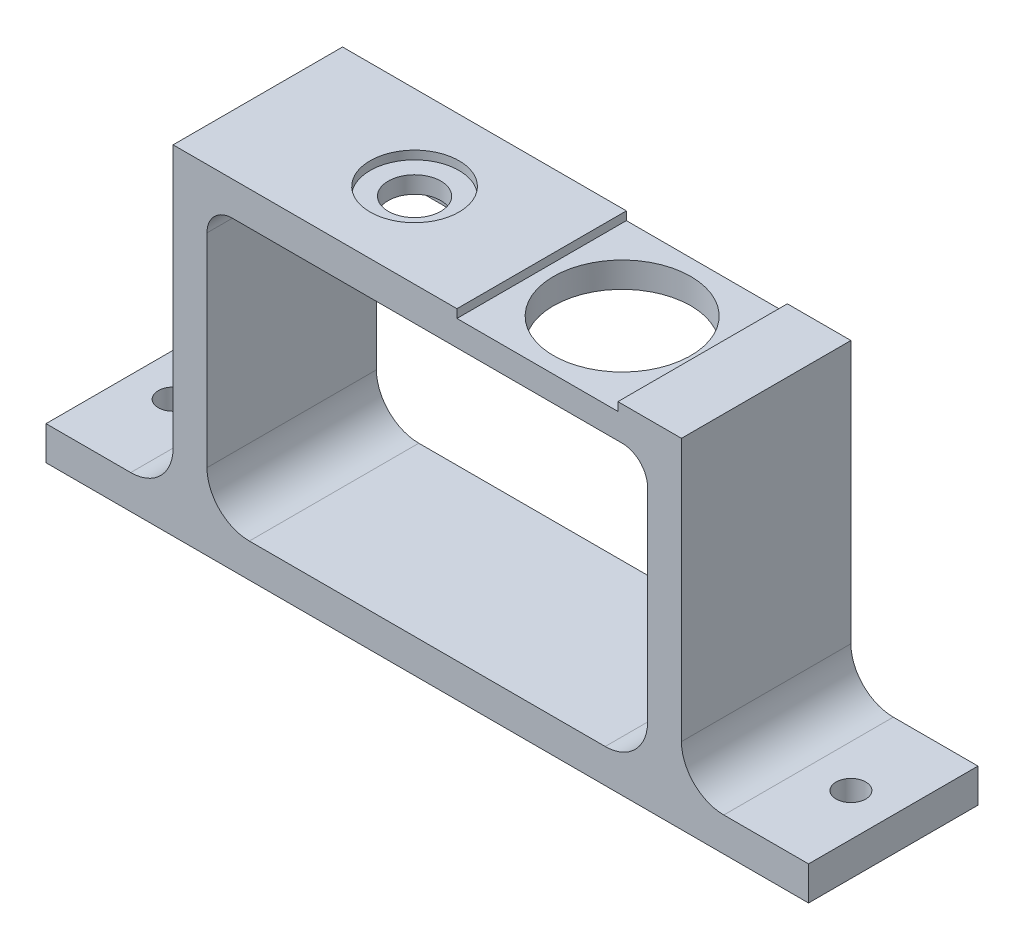
SolidWorks part; units mm, degrees
ref_plane "前视基准面" through (0, 0, 0) normal (0, 0, 1) x (1, 0, 0)
ref_plane "上视基准面" through (0, 0, 0) normal (0, 1, 0) x (1, 0, 0)
ref_plane "右视基准面" through (0, 0, 0) normal (1, 0, 0) x (0, 0, -1)
sketch "草图1" plane through (0, 0, 0) normal (0, 1, 0) x (1, 0, 0)
  line L0 (45, 10) -> (45, 29.8353) construction
  line L1 (0, 0) -> (90, 0)
  line L2 (0, 0) -> (0, 20)
  line L3 (0, 20) -> (90, 20)
  line L4 (90, 0) -> (90, 20)
  line L5 (0, 0) -> (90, 20) construction
  line L6 (0, 20) -> (90, 0) construction
  circle A0 centre (85, 10) radius 1.75
  circle A3 centre (5, 10) radius 1.75
  point P4 (45, 10)
  dimension "D4" = 5
  dimension "D5" = 3.5
  dimension "D7" = 10
  dimension "D1" = 20
  dimension "D2" = 90
extrude "凸台-拉伸1" add sketch "草图1" along normal blind 4
sketch "草图2" plane through (0, 4, 0) normal (0, 1, 0) x (1, 0, 0)
  line L0 (90, 20) -> (0, 20) construction
  line L1 (15, 20) -> (19, 20)
  line L2 (15, 20) -> (15, 0)
  line L3 (15, 0) -> (19, 0)
  line L4 (75, 20) -> (75, 0)
  line L5 (15, 20) -> (19, 18.6667) construction
  line L6 (15, 0) -> (19, 1.3333) construction
  line L7 (0, 0) -> (90, 0) construction
  line L8 (19, 20) -> (19, 0)
  line L9 (71, 0) -> (71, 20)
  line L10 (71, 20) -> (75, 20)
  line L11 (71, 1.3333) -> (75, 0) construction
  line L12 (71, 18.6667) -> (75, 20) construction
  line L13 (71, 0) -> (75, 0)
  circle A2 centre (5, 10) radius 1.75 construction
  circle A3 centre (85, 10) radius 1.75 construction
  point P4 (45, 10)
  dimension "D1" = 10
  dimension "D2" = 10
  dimension "D3" = 4
  dimension "D4" = 4
extrude "凸台-拉伸2" add sketch "草图2" along normal blind 32
sketch "草图3" plane through (0, 36, 0) normal (0, 1, 0) x (1, 0, 0)
  line L1 (15, 20) -> (75, 20)
  line L2 (15, 20) -> (15, 0)
  line L3 (15, 0) -> (75, 0)
  line L4 (75, 20) -> (75, 0)
  line L5 (15, 20) -> (75, 0) construction
  line L6 (15, 0) -> (75, 20) construction
  line L7 (71, 20) -> (71, 0) construction
  circle A1 centre (58, 10) radius 8.1
  point P4 (45, 10)
  dimension "D2" = 16.2
  dimension "D4" = 13
extrude "凸台-拉伸3" add sketch "草图3" along normal blind 4
fillet "圆角1" radius 5 4 edges at (75, 4, -10) (71, 4, -10) (15, 4, -10) (19, 4, -10)
fillet "圆角2" radius 3 2 edges at (71, 36, -10) (19, 36, -10)
sketch "草图4" plane through (0, 40, 0) normal (0, 1, 0) x (1, 0, 0)
  line L7 (48.5, 0) -> (67.5, 0)
  line L8 (48.5, 0) -> (48.5, 20)
  line L9 (48.5, 20) -> (67.5, 20)
  line L10 (67.5, 0) -> (67.5, 20)
  line L11 (48.5, 0) -> (67.5, 20) construction
  line L12 (48.5, 20) -> (67.5, 0) construction
  point P6 (58, 10)
  dimension "D1" = 20
  dimension "D2" = 19
extrude "切除-拉伸1" cut sketch "草图4" against normal blind 1
sketch "草图5" plane through (0, 40, 0) normal (0, 1, 0) x (1, 0, 0)
  line L0 (48.5, 20) -> (15, 20) construction
  line L2 (48.5, 20) -> (48.5, 0) construction
  circle A0 centre (33.5, 10) radius 3.1
  dimension "D1" = 6.2
  dimension "D2" = 10
  dimension "D3" = 15
extrude "切除-拉伸2" cut sketch "草图5" against normal blind 10
sketch "草图6" plane through (0, 36, 0) normal (0, -1, 0) x (1, 0, 0)
  line L1 (26.7, -13.75) -> (40.3, -13.75)
  line L2 (26.7, -13.75) -> (26.7, -6.25)
  line L3 (26.7, -6.25) -> (40.3, -6.25)
  line L4 (40.3, -13.75) -> (40.3, -6.25)
  line L5 (26.7, -13.75) -> (40.3, -6.25) construction
  line L6 (26.7, -6.25) -> (40.3, -13.75) construction
  point P0 (33.5, -10)
  dimension "D1" = 7.5
  dimension "D2" = 13.6
extrude "切除-拉伸3" cut sketch "草图6" against normal blind 1
sketch "草图7" plane through (0, 40, 0) normal (0, 1, 0) x (1, 0, 0)
  circle A0 centre (33.5, 10) radius 5.25
  dimension "D1" = 10.5
extrude "切除-拉伸4" cut sketch "草图7" against normal blind 1
